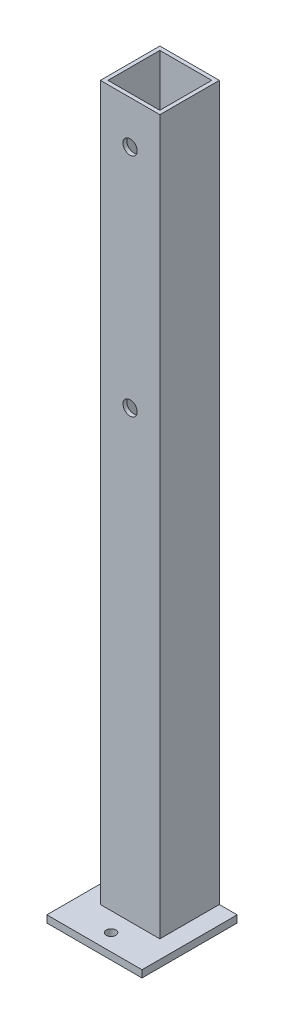
SolidWorks part; units mm, degrees
ref_plane "Front Plane" through (0, 0, 0) normal (0, 0, 1) x (1, 0, 0)
ref_plane "Top Plane" through (0, 0, 0) normal (0, 1, 0) x (1, 0, 0)
ref_plane "Right Plane" through (0, 0, 0) normal (1, 0, 0) x (0, 0, -1)
sketch "Sketch1" plane through (0, 0, 0) normal (0, 1, 0) x (1, 0, 0)
  line L0 (-10.9, 10.9) -> (10.9, 10.9)
  line L1 (-12.5, 12.5) -> (12.5, 12.5)
  line L2 (-12.5, 12.5) -> (-12.5, -12.5)
  line L3 (-12.5, -12.5) -> (12.5, -12.5)
  line L4 (12.5, 12.5) -> (12.5, -12.5)
  line L5 (10.9, 10.9) -> (10.9, -10.9)
  line L6 (-10.9, -10.9) -> (10.9, -10.9)
  line L7 (-10.9, 10.9) -> (-10.9, -10.9)
  point P4 (0, 12.5)
  point P7 (12.5, 0)
  dimension "D1" = 25
  dimension "D2" = 1.6
extrude "Boss-Extrude1" add sketch "Sketch1" along normal blind 300
sketch "Sketch2" plane through (0, 0, 0) normal (0, -1, 0) x (1, 0, 0)
  line L0 (12.5, -12.5) -> (-12.5, -12.5) construction
  line L1 (20, -12.5) -> (-20, -12.5)
  line L2 (20, -12.5) -> (20, 27.5)
  line L3 (20, 27.5) -> (-20, 27.5)
  line L4 (-20, -12.5) -> (-20, 27.5)
  line L5 (0, -1000) -> (0, 49000) construction
  dimension "D1" = 40
  dimension "D2" = 40
extrude "Boss-Extrude2" add sketch "Sketch2" along normal blind 3
sketch "Sketch3" plane through (0, 0, 12.5) normal (0, 0, 1) x (1, 0, 0)
  line L0 (-12.5, 300) -> (12.5, 300) construction
  line L1 (20, -3) -> (-20, -3) construction
  circle A0 centre (0, 187) radius 3
  circle A1 centre (0, 282) radius 3
  point P4 (0, 300)
  dimension "D1" = 6
  dimension "D3" = 6
  dimension "D2" = 190
  dimension "D4" = 95
extrude "Cut-Extrude1" cut sketch "Sketch3" against normal up to next
sketch "Sketch4" plane through (0, 0, 0) normal (0, 1, 0) x (1, 0, 0)
  line L0 (20, -27.5) -> (-20, -27.5) construction
  circle A0 centre (0, -20.5) radius 2
  point P4 (0, -27.5)
  dimension "D1" = 4
  dimension "D2" = 7
extrude "Cut-Extrude2" cut sketch "Sketch4" against normal up to next
